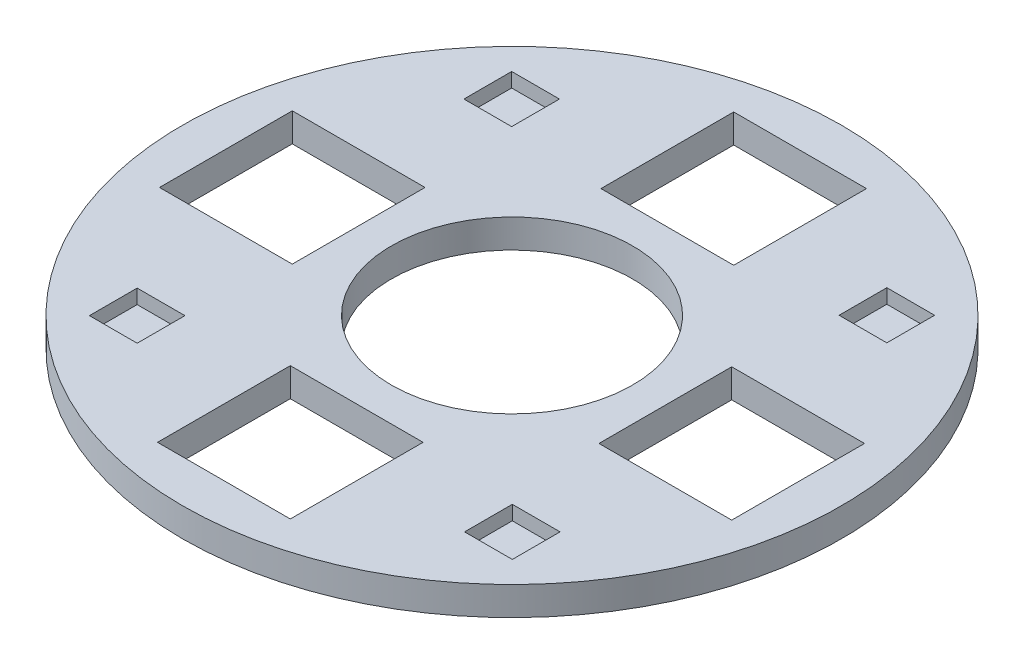
SolidWorks part; units mm, degrees
ref_plane "Front Plane" through (0, 0, 0) normal (0, 0, 1) x (1, 0, 0)
ref_plane "Top Plane" through (0, 0, 0) normal (0, 1, 0) x (1, 0, 0)
ref_plane "Right Plane" through (0, 0, 0) normal (1, 0, 0) x (0, 0, -1)
sketch "Sketch1" plane through (0, 0, 0) normal (0, 1, 0) x (1, 0, 0)
  circle A0 centre (0, 0) radius 34.5
  dimension "D1" = 69
extrude "Boss-Extrude1" add sketch "Sketch1" along normal blind 3
sketch "Sketch2" plane through (0, 3, 0) normal (0, 1, 0) x (1, 0, 0)
  line L0 (0, 0) -> (34.5, 0) construction
  line L1 (0, 0) -> (0, 34.5) construction
  line L2 (0, 0) -> (-34.5, 0) construction
  line L3 (0, 0) -> (0, -34.5) construction
  line L5 (-26.093, -3.0565) -> (-26.093, 3.1435)
  line L6 (-19.893, 3.1435) -> (-26.093, 3.1435)
  line L7 (-19.893, -3.0565) -> (-19.893, 3.1435)
  line L8 (-19.893, -3.0565) -> (-26.093, -3.0565)
  line L9 (-3.6156, 19.4138) -> (3.835, 19.4138)
  line L10 (-3.6156, 19.4138) -> (-3.6156, 26.8644)
  line L11 (-3.6156, 26.8644) -> (3.835, 26.8644)
  line L12 (3.835, 19.4138) -> (3.835, 26.8644)
  line L13 (-3.6156, 19.4138) -> (3.835, 26.8644) construction
  line L14 (-3.6156, 26.8644) -> (3.835, 19.4138) construction
  line L15 (3.2026, -26.1592) -> (-2.9974, -26.1592)
  line L16 (-2.9974, -19.9592) -> (-2.9974, -26.1592)
  line L17 (3.2026, -19.9592) -> (-2.9974, -19.9592)
  line L18 (3.2026, -19.9592) -> (3.2026, -26.1592)
  line L19 (26.3053, 3.1364) -> (26.3053, -3.0636)
  line L20 (20.1053, -3.0636) -> (26.3053, -3.0636)
  line L21 (20.1053, 3.1364) -> (20.1053, -3.0636)
  line L22 (20.1053, 3.1364) -> (26.3053, 3.1364)
  circle A0 centre (0, 0) radius 34.5 construction
  point P6 (0.1038, 23.1056)
  point P12 (0.1038, 23.1056)
sketch "Sketch3" plane through (0, 3, 0) normal (0, 1, 0) x (1, 0, 0)
  line L0 (16.1556, -7.0538) -> (16.1556, 6.8462)
  line L1 (7.0538, 30.0556) -> (-6.8462, 30.0556)
  line L2 (7.0538, 30.0556) -> (7.0538, 16.1556)
  line L3 (7.0538, 16.1556) -> (-6.8462, 16.1556)
  line L4 (-6.8462, 30.0556) -> (-6.8462, 16.1556)
  line L5 (7.0538, 30.0556) -> (-6.8462, 16.1556) construction
  line L6 (7.0538, 16.1556) -> (-6.8462, 30.0556) construction
  line L7 (30.0556, -7.0538) -> (16.1556, -7.0538)
  line L8 (30.0556, -7.0538) -> (30.0556, 6.8462)
  line L9 (30.0556, 6.8462) -> (16.1556, 6.8462)
  line L10 (-7.0538, -16.1556) -> (6.8462, -16.1556)
  line L11 (-7.0538, -30.0556) -> (-7.0538, -16.1556)
  line L12 (-7.0538, -30.0556) -> (6.8462, -30.0556)
  line L13 (6.8462, -30.0556) -> (6.8462, -16.1556)
  line L14 (-16.1556, 7.0538) -> (-16.1556, -6.8462)
  line L15 (-30.0556, 7.0538) -> (-16.1556, 7.0538)
  line L16 (-30.0556, 7.0538) -> (-30.0556, -6.8462)
  line L17 (-30.0556, -6.8462) -> (-16.1556, -6.8462)
  point P0 (0.1038, 23.1056)
  dimension "D1" = 13.9
  dimension "D2" = 13.9
  dimension "D3" = 4
extrude "Cut-Extrude1" cut sketch "Sketch3" against normal through all
sketch "Sketch4" plane through (0, 3, 0) normal (0, 1, 0) x (1, 0, 0)
  circle A0 centre (0, 0) radius 12.6272
extrude "Cut-Extrude2" cut sketch "Sketch4" against normal through all
sketch "Sketch5" plane through (0, 3, 0) normal (0, 1, 0) x (1, 0, 0)
  line L0 (-23.1056, 7.0538) -> (-23.1056, 25.6199) construction
  line L1 (-16.1556, 7.0538) -> (-30.0556, 7.0538) construction
  line L2 (0.1038, 23.1056) -> (-25.6199, 23.1056) construction
  line L3 (0, 0) -> (-24.416, 24.3743) construction
  line L4 (22.1032, 17.1367) -> (22.1032, 22.1367)
  line L5 (-17.1367, 22.1032) -> (-22.1367, 22.1032)
  line L6 (-17.1367, 22.1032) -> (-17.1367, 17.1032)
  line L7 (-17.1367, 17.1032) -> (-22.1367, 17.1032)
  line L8 (-22.1367, 22.1032) -> (-22.1367, 17.1032)
  line L9 (-17.1367, 22.1032) -> (-22.1367, 17.1032) construction
  line L10 (-17.1367, 17.1032) -> (-22.1367, 22.1032) construction
  line L11 (17.1032, 17.1367) -> (17.1032, 22.1367)
  line L12 (22.1032, 17.1367) -> (17.1032, 17.1367)
  line L13 (22.1032, 22.1367) -> (17.1032, 22.1367)
  line L14 (17.1367, -22.1032) -> (22.1367, -22.1032)
  line L15 (17.1367, -17.1032) -> (22.1367, -17.1032)
  line L16 (17.1367, -22.1032) -> (17.1367, -17.1032)
  line L17 (22.1367, -22.1032) -> (22.1367, -17.1032)
  line L18 (-22.1032, -17.1367) -> (-22.1032, -22.1367)
  line L19 (-17.1032, -17.1367) -> (-17.1032, -22.1367)
  line L20 (-22.1032, -17.1367) -> (-17.1032, -17.1367)
  line L21 (-22.1032, -22.1367) -> (-17.1032, -22.1367)
  circle A0 centre (0, 0) radius 34.5 construction
  point P12 (-19.6367, 19.6032)
  dimension "D1" = 5
  dimension "D2" = 5
  dimension "D3" = 4
extrude "Cut-Extrude3" cut sketch "Sketch5" against normal blind 1.5
